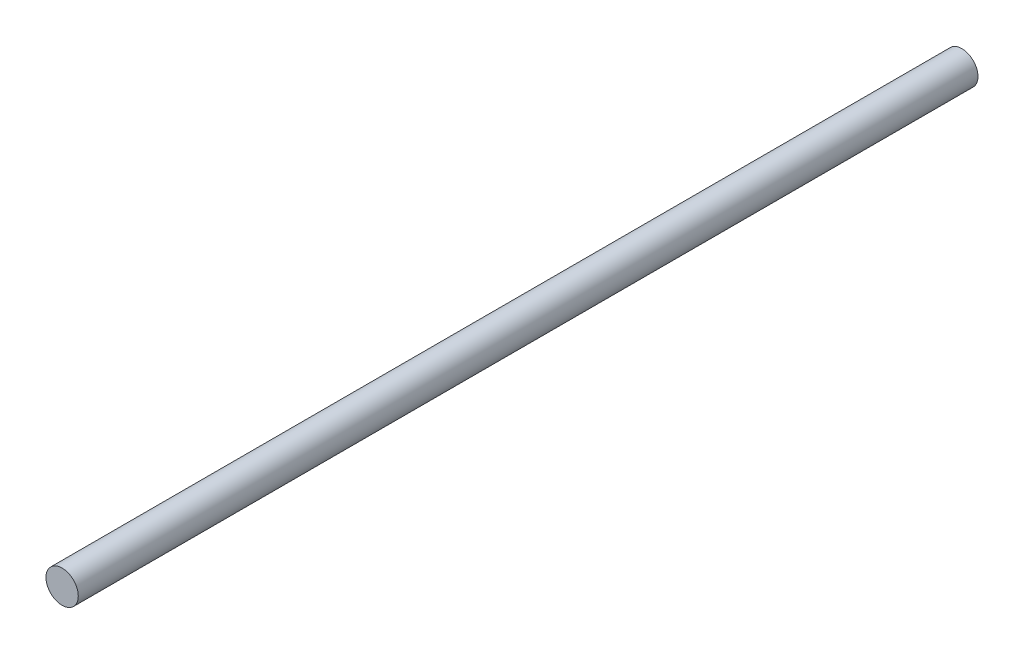
SolidWorks part; units mm, degrees
ref_plane "Front Plane" through (0, 0, 0) normal (0, 0, 1) x (1, 0, 0)
ref_plane "Top Plane" through (0, 0, 0) normal (0, 1, 0) x (1, 0, 0)
ref_plane "Right Plane" through (0, 0, 0) normal (1, 0, 0) x (0, 0, -1)
sketch "Sketch1" plane through (0, 0, 0) normal (0, 0, 1) x (1, 0, 0)
  circle A0 centre (0, 0) radius 50.8
  dimension "D1" = 101.6
extrude "Boss-Extrude1" add sketch "Sketch1" along normal blind 2828.544 contours A0
